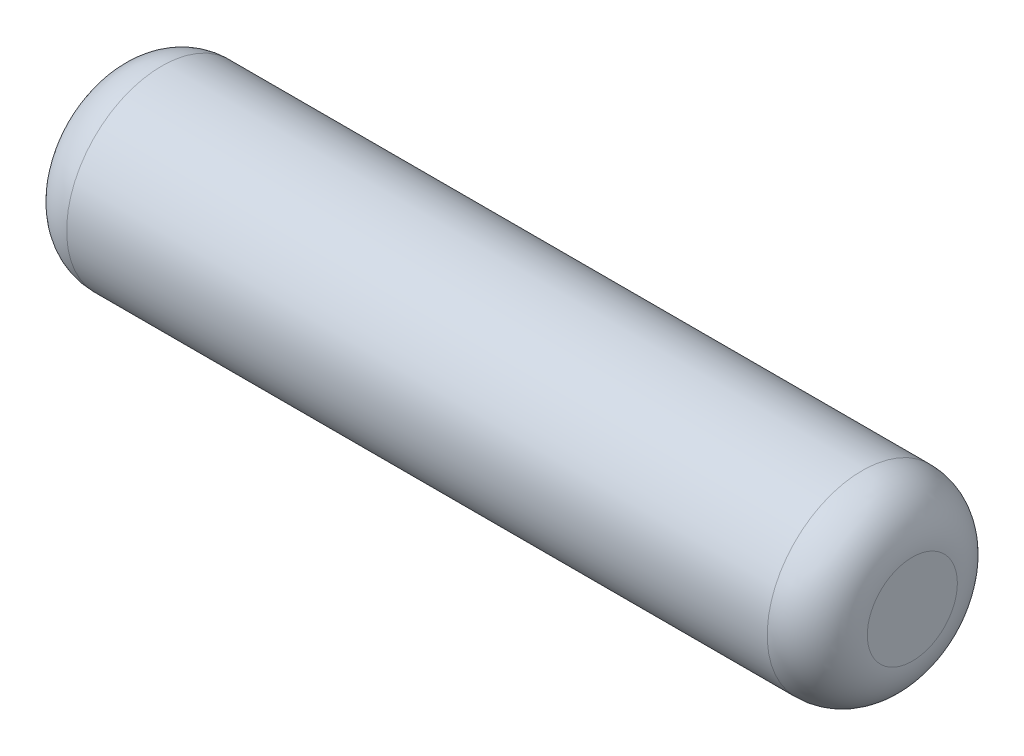
SolidWorks part; units mm, degrees
ref_plane "Front Plane" through (0, 0, 0) normal (0, 0, 1) x (1, 0, 0)
ref_plane "Top Plane" through (0, 0, 0) normal (0, 1, 0) x (1, 0, 0)
ref_plane "Right Plane" through (0, 0, 0) normal (1, 0, 0) x (0, 0, -1)
sketch "Sketch1" plane through (0, 0, 0) normal (1, 0, 0) x (0, 0, -1)
  circle A0 centre (0, 0) radius 48.26
  dimension "D1" = 96.52
extrude "Boss-Extrude1" add sketch "Sketch1" along normal blind 406.4
fillet "Fillet1" radius 25.4 2 edges at (406.4, 0, -48.26) (0, 0, -48.26)
